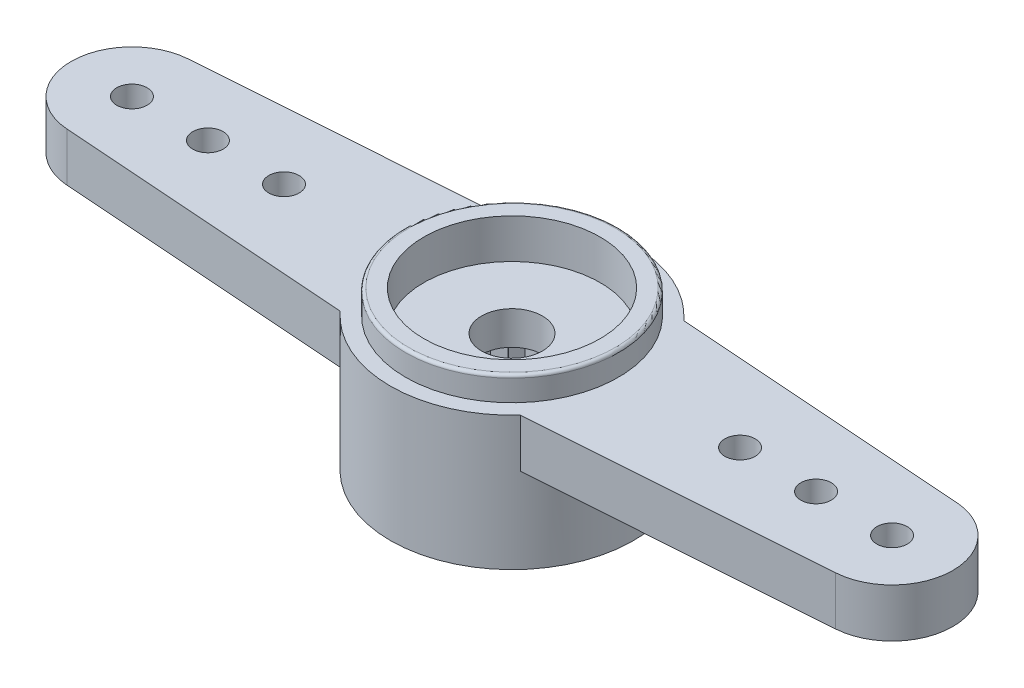
SolidWorks part; units mm, degrees
ref_plane "Front Plane" through (0, 0, 0) normal (0, 0, 1) x (1, 0, 0)
ref_plane "Top Plane" through (0, 0, 0) normal (0, 1, 0) x (1, 0, 0)
ref_plane "Right Plane" through (0, 0, 0) normal (1, 0, 0) x (0, 0, -1)
sketch "Sketch1" plane through (0, 0, 0) normal (0, 1, 0) x (1, 0, 0)
  circle A0 centre (0, 0) radius 4
  circle A1 centre (0, 0) radius 2.6
  dimension "D1" = 8
  dimension "D2" = 5.2
extrude "Boss-Extrude1" add sketch "Sketch1" along normal blind 4.4
sketch "Sketch2" plane through (0, 4.4, 0) normal (0, 1, 0) x (1, 0, 0)
  line L0 (0, 0) -> (50000, 0) construction
  line L1 (0, 0) -> (0, 50000) construction
  line L2 (0, 2.9) -> (12.6428, 1.9949)
  line L3 (0, -2.9) -> (12.6428, -1.9949)
  line L4 (0, -2.9) -> (-12.6428, -1.9949)
  line L5 (0, 2.9) -> (-12.6428, 1.9949)
  circle A0 centre (12.5, 0) radius 0.5
  circle A1 centre (10, 0) radius 0.5
  circle A2 centre (7.5, 0) radius 0.5
  arc A3 (-12.6428, -1.9949) -> (-12.6428, 1.9949) centre (-12.5, 0) cw
  arc A4 (12.6428, -1.9949) -> (12.6428, 1.9949) centre (12.5, 0) ccw
  circle A5 centre (0, 0) radius 2.9 construction
  circle A6 centre (-7.5, 0) radius 0.5
  circle A7 centre (-10, 0) radius 0.5
  circle A8 centre (-12.5, 0) radius 0.5
  circle A11 centre (0, 0) radius 1
  dimension "D1" = 3
  dimension "D3" = 4
  dimension "D4" = 5.8
  dimension "D5" = 2
  dimension "D2" = 12.5
extrude "Boss-Extrude2" add sketch "Sketch2" against normal blind 1.6
sketch "Sketch3" plane through (0, 4.4, 0) normal (0, -1, 0) x (-1, 0, 0)
  circle A0 centre (0, 0) radius 3.5
  dimension "D1" = 7
extrude "Boss-Extrude3" add sketch "Sketch3" against normal blind 0.8
sketch "Sketch4" plane through (0, 5.2, 0) normal (0, 1, 0) x (1, 0, 0)
  circle A0 centre (0, 0) radius 2.9
extrude "Cut-Extrude1" cut sketch "Sketch4" against normal blind 1.3
fillet "Fillet1" radius 0.1 1 edges at (0, 5.2, -3.5)
sketch "Sketch5" plane through (0, 0, 0) normal (0, -1, 0) x (1, 0, 0)
  line L1 (0, 2.8602) -> (0, 0.0102) construction
  line L6 (-0.4662, 2.4602) -> (0.4662, 2.4602)
  line L7 (0, 2.9264) -> (0.4662, 2.4602)
  line L8 (0, 2.9264) -> (-0.4662, 2.4602)
  circle A0 centre (0, 0.0102) radius 2.45 construction
  circle A1 centre (0, 0.0102) radius 2.85 construction
  dimension "D1" = 4.9
extrude "Cut-Extrude2" cut sketch "Sketch5" against normal blind 2.8
pattern_circular "CirPattern1" count 23 over 360 about axis through (0, 0, 0) along (0, 1, 0) of "Cut-Extrude2"
